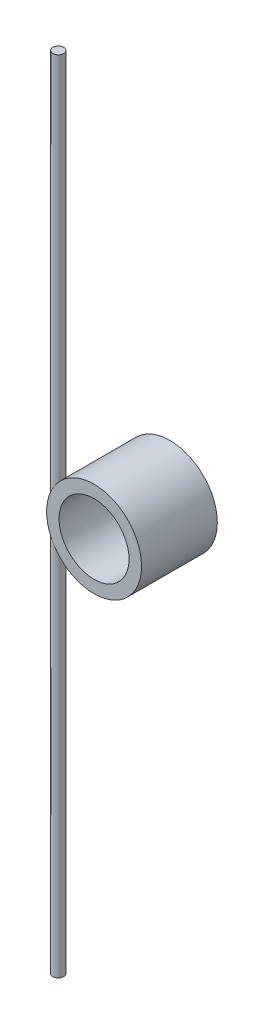
SolidWorks part; units mm, degrees
ref_plane "Ebene vorne" through (0, 0, 0) normal (0, 0, 1) x (1, 0, 0)
ref_plane "Ebene oben" through (0, 0, 0) normal (0, 1, 0) x (1, 0, 0)
ref_plane "Ebene rechts" through (0, 0, 0) normal (1, 0, 0) x (0, 0, -1)
sketch "Sketch1" plane through (0, 0, 0) normal (0, 0, 1) x (1, 0, 0)
  circle A0 centre (0, 0) radius 4.2
  circle A1 centre (0, 0) radius 5.7
  dimension "D1" = 8.4
  dimension "D2" = 11.4
extrude "Boss-Extrude1" add sketch "Sketch1" along normal blind 9.1
sketch "Sketch2" plane through (0, 0, 0) normal (0, 1, 0) x (1, 0, 0)
  circle A0 centre (-4.9488, -8.4447) radius 0.65
  point P2 (-4.9488, -8.4447)
  dimension "D1" = 1.3
extrude "Boss-Extrude2" add sketch "Sketch2" along normal mid plane 96 contours A0
